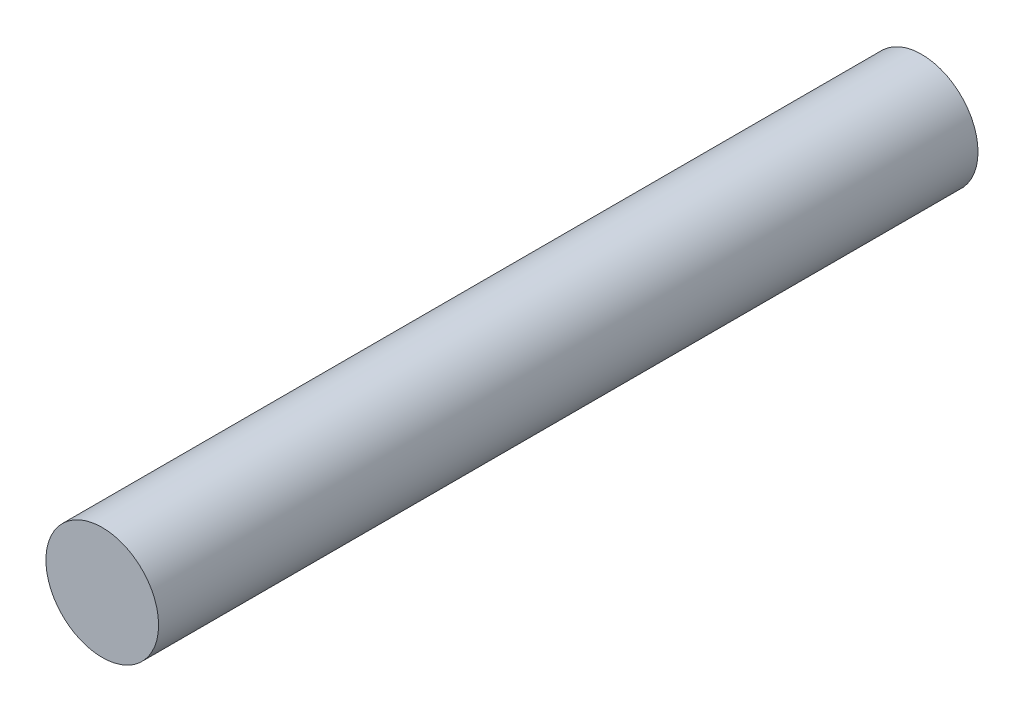
SolidWorks part; units mm, degrees
ref_plane "前视基准面" through (0, 0, 0) normal (0, 0, 1) x (1, 0, 0)
ref_plane "上视基准面" through (0, 0, 0) normal (0, 1, 0) x (1, 0, 0)
ref_plane "右视基准面" through (0, 0, 0) normal (1, 0, 0) x (0, 0, -1)
sketch "草图1" plane through (0, 0, 0) normal (0, 0, 1) x (1, 0, 0)
  circle A0 centre (0, 0) radius 4
extrude "凸台-拉伸1" add sketch "草图1" along normal blind 58.18
